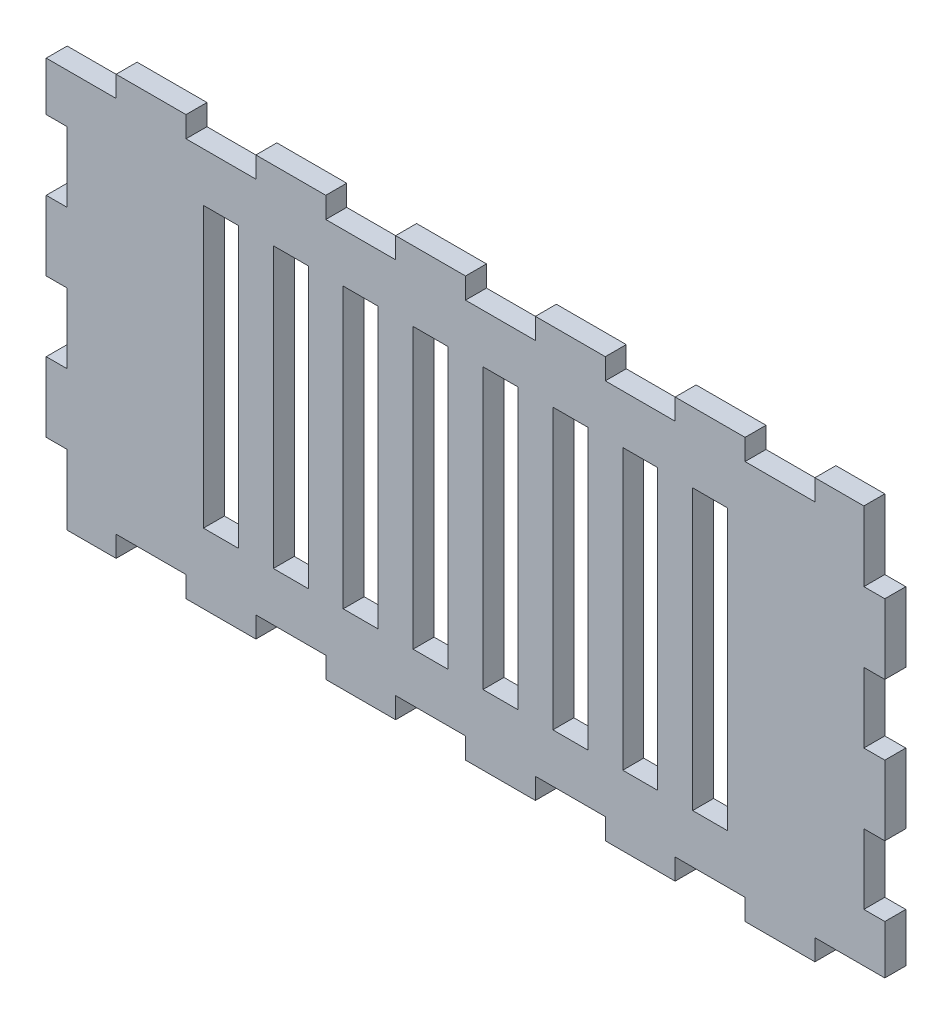
SolidWorks part; units mm, degrees
material "Beech"
ref_plane "Front Plane" through (0, 0, 0) normal (0, 0, 1) x (1, 0, 0)
ref_plane "Top Plane" through (0, 0, 0) normal (0, 1, 0) x (1, 0, 0)
ref_plane "Right Plane" through (0, 0, 0) normal (1, 0, 0) x (0, 0, -1)
sketch "Sketch1" plane through (0, 0, 0) normal (0, 0, 1) x (1, 0, 0)
  line L0 (120, 10) -> (117, 10)
  line L1 (0, 0) -> (120, 0)
  line L2 (0, 0) -> (0, 60)
  line L3 (0, 60) -> (120, 60)
  line L4 (120, 0) -> (120, 60)
  line L5 (117, 10) -> (117, 20)
  line L6 (117, 20) -> (120, 20)
  line L7 (117, 40) -> (120, 40)
  line L8 (117, 30) -> (117, 40)
  line L9 (120, 30) -> (117, 30)
  line L10 (117, 60) -> (120, 60)
  line L11 (117, 50) -> (117, 60)
  line L12 (120, 50) -> (117, 50)
  line L13 (10, 0) -> (10, 3)
  line L14 (10, 3) -> (20, 3)
  line L15 (20, 3) -> (20, 0)
  line L16 (30, 0) -> (30, 3)
  line L17 (40, 3) -> (40, 0)
  line L18 (30, 3) -> (40, 3)
  line L19 (50, 0) -> (50, 3)
  line L20 (60, 3) -> (60, 0)
  line L21 (50, 3) -> (60, 3)
  line L22 (70, 0) -> (70, 3)
  line L23 (80, 3) -> (80, 0)
  line L24 (70, 3) -> (80, 3)
  line L25 (90, 0) -> (90, 3)
  line L26 (100, 3) -> (100, 0)
  line L27 (90, 3) -> (100, 3)
  line L28 (110, 0) -> (110, 3)
  line L29 (120, 3) -> (120, 0)
  line L30 (0, 60) -> (0, 57)
  line L31 (0, 57) -> (10, 57)
  line L32 (120, 60) -> (120, 57)
  line L33 (10, 57) -> (10, 60)
  line L34 (0, 50) -> (3, 50)
  line L35 (3, 50) -> (3, 40)
  line L36 (3, 40) -> (0, 40)
  line L37 (3, 20) -> (0, 20)
  line L38 (3, 30) -> (3, 20)
  line L39 (0, 30) -> (3, 30)
  line L40 (3, 0) -> (0, 0)
  line L41 (3, 10) -> (3, 0)
  line L42 (0, 10) -> (3, 10)
  line L43 (30, 57) -> (30, 60)
  line L44 (20, 57) -> (30, 57)
  line L45 (20, 60) -> (20, 57)
  line L46 (50, 57) -> (50, 60)
  line L47 (40, 57) -> (50, 57)
  line L48 (40, 60) -> (40, 57)
  line L49 (70, 57) -> (70, 60)
  line L50 (60, 57) -> (70, 57)
  line L51 (60, 60) -> (60, 57)
  line L52 (90, 57) -> (90, 60)
  line L53 (80, 57) -> (90, 57)
  line L54 (80, 60) -> (80, 57)
  line L55 (110, 57) -> (110, 60)
  line L56 (110, 3) -> (120, 3)
  line L57 (100, 57) -> (110, 57)
  line L58 (100, 60) -> (100, 57)
  dimension "D1" = 120
  dimension "D2" = 60
  dimension "D3" = 10
  dimension "D4" = 10
  dimension "D5" = 10
  dimension "D7" = 10
  dimension "D8" = 3
  dimension "D9" = 0
  dimension "D11" = 10
  dimension "D12" = 10
  dimension "D13" = 3
  dimension "D10" = 10
  dimension "D14" = 3
  dimension "D6" = 3
extrude "Boss-Extrude1" add sketch "Sketch1" along normal blind 3
sketch "Sketch2" plane through (0, 0, 3) normal (0, 0, 1) x (1, 0, 0)
  line L0 (10, 60) -> (20, 60) construction
  line L1 (22.5, 50) -> (27.5, 50)
  line L2 (22.5, 50) -> (22.5, 10)
  line L3 (22.5, 10) -> (27.5, 10)
  line L4 (27.5, 50) -> (27.5, 10)
  line L5 (0, 30) -> (0, 40) construction
  line L6 (32.5, 50) -> (37.5, 50)
  line L7 (37.5, 50) -> (37.5, 10)
  line L8 (32.5, 50) -> (32.5, 10)
  line L9 (32.5, 10) -> (37.5, 10)
  line L10 (42.5, 50) -> (47.5, 50)
  line L11 (47.5, 50) -> (47.5, 10)
  line L12 (42.5, 50) -> (42.5, 10)
  line L13 (42.5, 10) -> (47.5, 10)
  line L14 (52.5, 50) -> (57.5, 50)
  line L15 (57.5, 50) -> (57.5, 10)
  line L16 (52.5, 50) -> (52.5, 10)
  line L17 (52.5, 10) -> (57.5, 10)
  line L18 (62.5, 50) -> (67.5, 50)
  line L19 (67.5, 50) -> (67.5, 10)
  line L20 (62.5, 50) -> (62.5, 10)
  line L21 (62.5, 10) -> (67.5, 10)
  line L22 (72.5, 50) -> (77.5, 50)
  line L23 (77.5, 50) -> (77.5, 10)
  line L24 (72.5, 50) -> (72.5, 10)
  line L25 (72.5, 10) -> (77.5, 10)
  line L26 (82.5, 50) -> (87.5, 50)
  line L27 (87.5, 50) -> (87.5, 10)
  line L28 (82.5, 50) -> (82.5, 10)
  line L29 (82.5, 10) -> (87.5, 10)
  line L30 (92.5, 50) -> (97.5, 50)
  line L31 (97.5, 50) -> (97.5, 10)
  line L32 (92.5, 50) -> (92.5, 10)
  line L33 (92.5, 10) -> (97.5, 10)
  line L34 (120, 40) -> (120, 50) construction
  point P4 (25, 50)
  dimension "D1" = 5
  dimension "D2" = 40
  dimension "D3" = 10
  dimension "D4" = 22.5
  dimension "D6" = 22.5
  dimension "D5" = 8
extrude "Cut-Extrude1" cut sketch "Sketch2" against normal blind 10
